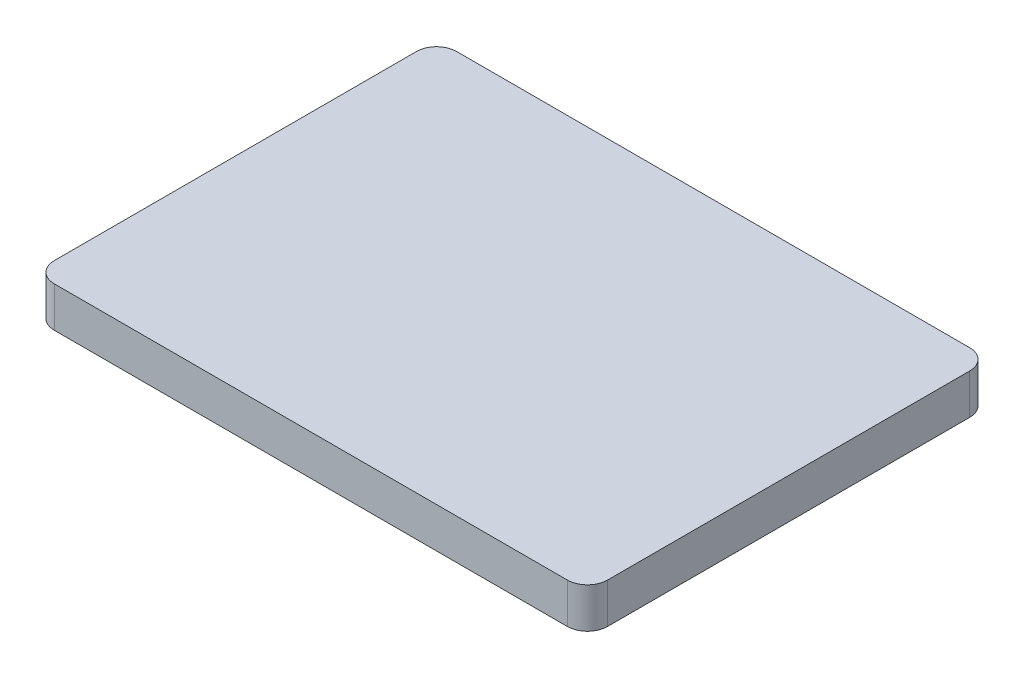
SolidWorks part; units mm, degrees
ref_plane "Front Plane" through (0, 0, 0) normal (0, 0, 1) x (1, 0, 0)
ref_plane "Top Plane" through (0, 0, 0) normal (0, 1, 0) x (1, 0, 0)
ref_plane "Right Plane" through (0, 0, 0) normal (1, 0, 0) x (0, 0, -1)
sketch "Sketch1" plane through (0, 0, 0) normal (0, 1, 0) x (1, 0, 0)
  line L1 (-2.75, -2) -> (2.75, -2)
  line L2 (-2.75, -2) -> (-2.75, 2)
  line L3 (-2.75, 2) -> (2.75, 2)
  line L4 (2.75, -2) -> (2.75, 2)
  line L5 (-2.75, -2) -> (2.75, 2) construction
  line L6 (-2.75, 2) -> (2.75, -2) construction
  point P0 (0, 0)
  dimension "D1" = 4
  dimension "D2" = 5.5
extrude "Boss-Extrude1" add sketch "Sketch1" along normal blind 0.4
fillet "Fillet1" radius 0.2 4 edges at (2.75, 0.2, -2) (2.75, 0.2, 2) (-2.75, 0.2, 2) (-2.75, 0.2, -2)
